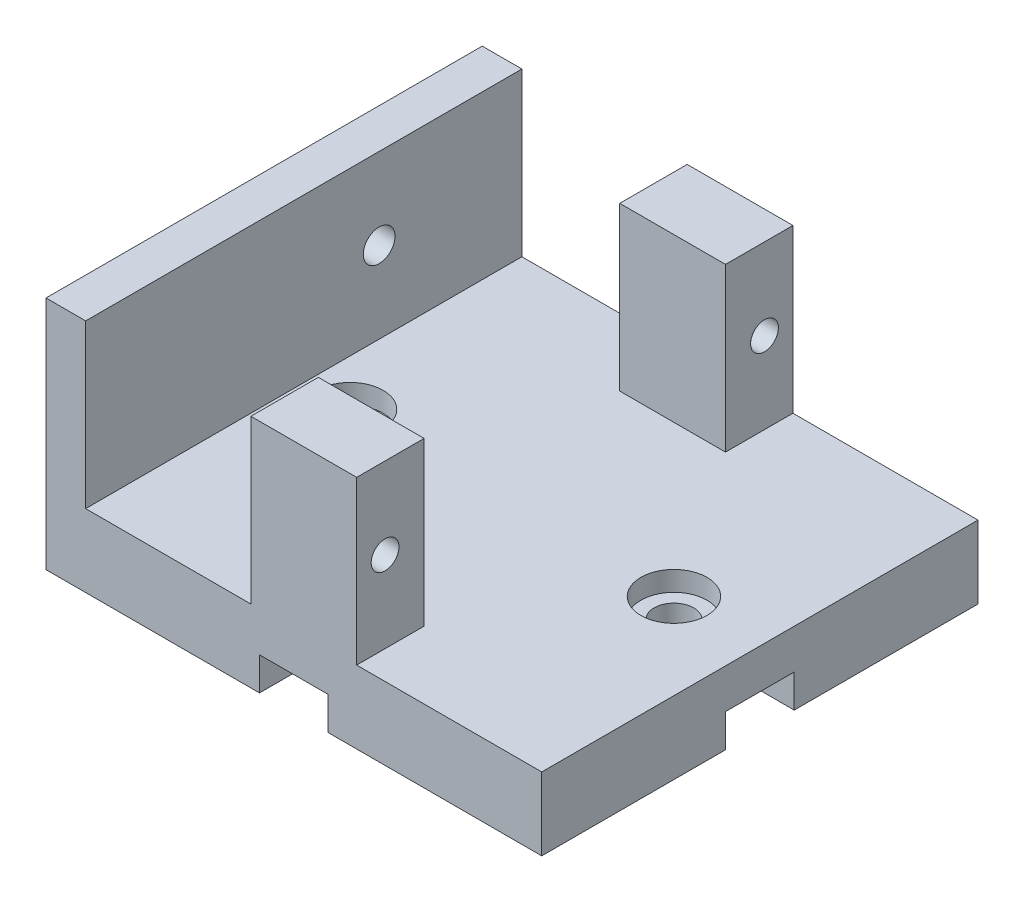
SolidWorks part; units mm, degrees
ref_plane "Ebene vorne" through (0, 0, 0) normal (0, 0, 1) x (1, 0, 0)
ref_plane "Ebene oben" through (0, 0, 0) normal (0, 1, 0) x (1, 0, 0)
ref_plane "Ebene rechts" through (0, 0, 0) normal (1, 0, 0) x (0, 0, -1)
sketch "Skizze1" plane through (0, 0, 0) normal (0, 1, 0) x (1, 0, 0)
  line L1 (-18.75, -16.5) -> (18.75, -16.5)
  line L2 (-18.75, -16.5) -> (-18.75, 16.5)
  line L3 (-18.75, 16.5) -> (18.75, 16.5)
  line L4 (18.75, -16.5) -> (18.75, 16.5)
  line L5 (-18.75, -16.5) -> (18.75, 16.5) construction
  line L6 (-18.75, 16.5) -> (18.75, -16.5) construction
  point P0 (0, 0)
  dimension "D1" = 37.5
  dimension "D2" = 33
extrude "Aufsatz-Linear austragen1" add sketch "Skizze1" along normal blind 2.5 and the other way blind 3
sketch "Skizze2" plane through (0, 2.5, 0) normal (0, 1, 0) x (1, 0, 0)
  line L0 (-18.75, -16.5) -> (18.75, -16.5) construction
  line L1 (-18.75, 16.5) -> (-15.75, 16.5)
  line L2 (-18.75, 16.5) -> (-18.75, -16.5)
  line L3 (-18.75, -16.5) -> (-15.75, -16.5)
  line L4 (-15.75, 16.5) -> (-15.75, -16.5)
  line L5 (18.75, 16.5) -> (-18.75, 16.5) construction
  line L6 (4.75, -16.5) -> (-3.25, -16.5)
  line L7 (4.75, -16.5) -> (4.75, -11.4)
  line L8 (4.75, -11.4) -> (-3.25, -11.4)
  line L9 (-3.25, -16.5) -> (-3.25, -11.4)
  line L10 (4.75, 16.5) -> (-3.25, 16.5)
  line L11 (4.75, 16.5) -> (4.75, 11.4)
  line L12 (4.75, 11.4) -> (-3.25, 11.4)
  line L13 (-3.25, 16.5) -> (-3.25, 11.4)
  dimension "D1" = 3
  dimension "D2" = 20.5
  dimension "D3" = 8
  dimension "D4" = 8
  dimension "D5" = 20.5
  dimension "D6" = 5.1
  dimension "D7" = 5.1
  dimension "D8" = 22.8
extrude "Aufsatz-Linear austragen2" add sketch "Skizze2" along normal blind 12.3
sketch "Skizze5" plane through (-15.75, 0, 0) normal (1, 0, 0) x (0, 0, -1)
  line L0 (-16.5, 14.8) -> (16.5, 14.8) construction
  line L4 (16.5, 14.8) -> (16.5, 2.5) construction
  circle A1 centre (5.7, 8.65) radius 1.2
  dimension "D2" = 6.15
  dimension "D1" = 2.4
  dimension "D3" = 10.8
extrude "Schnitt-Linear austragen4" cut sketch "Skizze5" against normal through all
sketch "Skizze7" plane through (4.75, 0, 0) normal (1, 0, 0) x (0, 0, -1)
  line L0 (16.5, 14.8) -> (16.5, 2.5) construction
  line L1 (16.5, 2.5) -> (16.5, 8.65) construction
  line L2 (16.5, 8.65) -> (-16.5, 8.65) construction
  line L3 (-16.5, 14.8) -> (-16.5, 2.5) construction
  line L4 (13.3, 8.65) -> (13.3, 6.1689) construction
  line L5 (-13.3, 8.65) -> (-13.3, 6.1689) construction
  circle A0 centre (-14.35, 8.65) radius 1.05
  circle A1 centre (14.35, 8.65) radius 1.05
  dimension "D1" = 2.1
  dimension "D2" = 2.1
  dimension "D3" = 3.2
  dimension "D4" = 3.2
extrude "Schnitt-Linear austragen5" cut sketch "Skizze7" against normal blind 10
sketch "Skizze8" plane through (0, -3, 0) normal (0, -1, 0) x (1, 0, 0)
  line L0 (-2.6, -5.75) -> (2.6, -5.75)
  line L1 (5.75, -2.6) -> (18.75, -2.6)
  line L2 (5.75, -2.6) -> (5.75, 2.6)
  line L3 (5.75, 2.6) -> (18.75, 2.6)
  line L4 (18.75, -2.6) -> (18.75, 2.6)
  line L5 (5.75, -2.6) -> (18.75, 2.6) construction
  line L6 (5.75, 2.6) -> (18.75, -2.6) construction
  line L7 (-2.6, -5.75) -> (-2.6, -18.75)
  line L8 (-2.6, -18.75) -> (2.6, -18.75)
  line L9 (2.6, -5.75) -> (2.6, -18.75)
  line L10 (-5.75, 2.6) -> (-5.75, -2.6)
  line L11 (-5.75, 2.6) -> (-18.75, 2.6)
  line L12 (-18.75, 2.6) -> (-18.75, -2.6)
  line L13 (-5.75, -2.6) -> (-18.75, -2.6)
  line L14 (2.6, 5.75) -> (-2.6, 5.75)
  line L15 (2.6, 5.75) -> (2.6, 18.75)
  line L16 (2.6, 18.75) -> (-2.6, 18.75)
  line L17 (-2.6, 5.75) -> (-2.6, 18.75)
  line L18 (-18.75, 16.5) -> (18.75, 16.5) construction
  point P3 (12.25, 0)
  point P23 (0, 0)
  dimension "D3" = 12.25
  dimension "D1" = 13
  dimension "D2" = 5.2
  dimension "D5" = 16.5
  dimension "D4" = 4
extrude "Schnitt-Linear austragen6" cut sketch "Skizze8" against normal blind 2.5
sketch "Skizze10" plane through (0, 0, 0) normal (0, 1, 0) x (-1, 0, 0)
  line L5 (10.8573, -0.5571) -> (13.6427, 0.5571) construction
  line L6 (11.9373, 1.467) -> (12.5627, -1.467) construction
  circle A0 centre (12.25, 0) radius 1.5
  circle A2 centre (-12.25, 0) radius 1.5
  circle A4 centre (0, 12.25) radius 1.5 [skipped]
  circle A5 centre (0, -12.25) radius 1.5 [skipped]
  point P3 (12.25, 0)
  point P23 (0, 0)
  point P29 (0, 0)
  dimension "D3" = 12.25
  dimension "D5" = 3
  dimension "D6" = 4
extrude "Schnitt-Linear austragen7" cut sketch "Skizze10" against normal through all and the other way through all contours A2 | A0
sketch "Skizze13" plane through (0, 2.5, 0) normal (0, 1, 0) x (-1, 0, 0)
  line L5 (9.9288, -0.9285) -> (14.5712, 0.9285) construction
  line L6 (11.7288, 2.4451) -> (12.7712, -2.4451) construction
  line L7 (9.79, 0) -> (-9.79, 0) construction
  line L8 (0, 9.79) -> (0, -9.79) construction
  circle A0 centre (12.25, 0) radius 2.5
  circle A4 centre (12.25, 0) radius 1.5 construction
  circle A5 centre (-12.25, 0) radius 2.5
  point P3 (12.25, 0)
  point P23 (0, 0)
  dimension "D3" = 12.25
  dimension "D5" = 5
  dimension "D1" = 0
  dimension "D2" = 0
extrude "Schnitt-Linear austragen8" cut sketch "Skizze13" against normal blind 1.5
